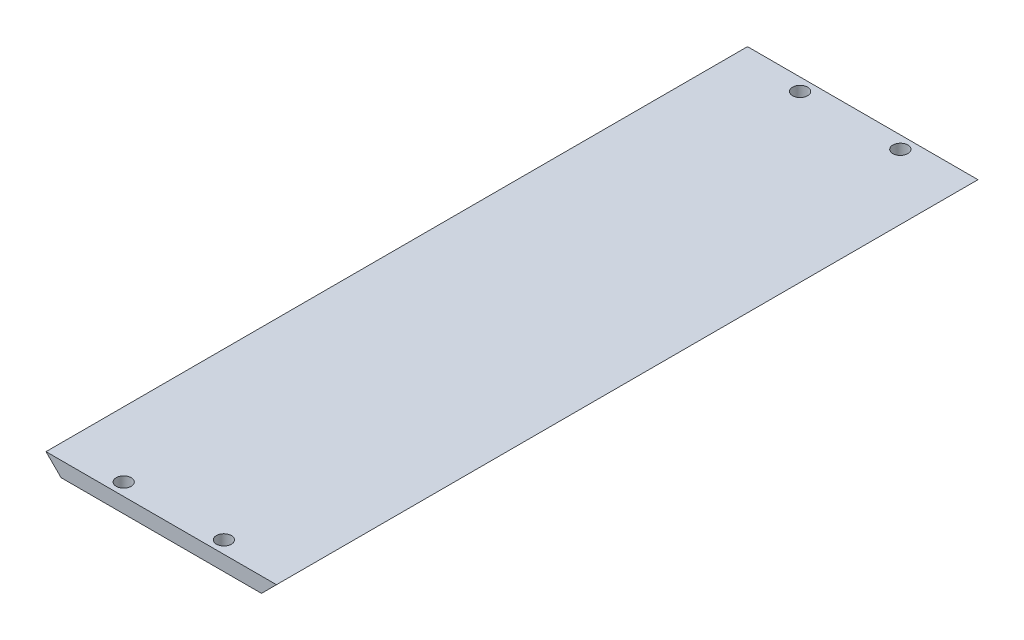
SolidWorks part; units mm, degrees
material "PET"
ref_plane "Front Plane" through (0, 0, 0) normal (0, 0, 1) x (1, 0, 0)
ref_plane "Top Plane" through (0, 0, 0) normal (0, 1, 0) x (1, 0, 0)
ref_plane "Right Plane" through (0, 0, 0) normal (1, 0, 0) x (0, 0, -1)
sketch "Sketch1" plane through (0, 0, 0) normal (0, 1, 0) x (1, 0, 0)
  line L1 (-25, -70) -> (25, -70)
  line L2 (-25, -70) -> (-25, 70)
  line L3 (-25, 70) -> (25, 70)
  line L4 (25, -70) -> (25, 70)
  line L5 (-25, -70) -> (25, 70) construction
  line L6 (-25, 70) -> (25, -70) construction
  point P0 (0, 0)
  dimension "D1" = 50
  dimension "D2" = 140
extrude "Boss-Extrude2" add sketch "Sketch1" along normal blind 5
sketch "Sketch2" plane through (0, 0, 70) normal (0, 0, 1) x (1, 0, 0)
  line L0 (-25, 0) -> (25, 0) construction
  line L5 (-25, 5) -> (-20, 0)
  line L7 (25, 5) -> (20, 0)
  line M2 (-25, 0) -> (25, 0)
  line M3 (25, 0) -> (25, 5)
  line M5 (-25, 5) -> (-25, 0)
extrude "Cut-Extrude1" cut sketch "Sketch2" against normal blind 152 contours L5 M5 M2 | L7 M3 M2
sketch "Sketch7" plane through (0, 0, -70) normal (0, 0, -1) x (-1, 0, 0)
  line L1 (-25, 5) -> (25, 5)
  line L2 (-25, 5) -> (-25, 3)
  line L3 (-25, 3) -> (25, 3)
  line L4 (25, 5) -> (25, 3)
  dimension "D1" = 2
extrude "Cut-Extrude5" cut sketch "Sketch7" against normal blind 197
sketch "Sketch8" plane through (0, 0, 0) normal (0, -1, 0) x (1, 0, 0)
  line L1 (-15, -65) -> (15, -65)
  line L2 (-15, -65) -> (-15, 65)
  line L3 (-15, 65) -> (15, 65)
  line L4 (15, -65) -> (15, 65)
  line L5 (-15, -65) -> (15, 65) construction
  line L6 (-15, 65) -> (15, -65) construction
  point P0 (0, 0)
  dimension "D1" = 30
  dimension "D2" = 130
extrude "Cut-Extrude6" cut sketch "Sketch8" against normal blind 197
sketch "Sketch9" plane through (0, 0, 0) normal (0, -1, 0) x (1, 0, 0)
  line L0 (20, 70) -> (20, -70) construction
  line L1 (-20, -70) -> (20, -70)
  line L2 (-20, -70) -> (-20, -50)
  line L3 (-20, -50) -> (20, -50)
  line L4 (20, -70) -> (20, -50)
  circle A0 centre (-13.5, -56.5) radius 1.5
  circle A1 centre (13.5, -56.5) radius 1.5
  dimension "D1" = 20
extrude "Boss-Extrude5" add sketch "Sketch9" against normal blind 3
sketch "Sketch10" plane through (0, 0, 0) normal (0, -1, 0) x (1, 0, 0)
  line L0 (15, -50) -> (15, 65) construction
  line L5 (-20, 70) -> (-20, -70) construction
  line L6 (-15, 55) -> (15, 55)
  line L7 (-15, 55) -> (-15, 45)
  line L8 (-15, 45) -> (15, 45)
  line L9 (15, 55) -> (15, 45)
  line L10 (-20, 55) -> (20, 55)
  line L11 (-20, 55) -> (-20, 45)
  line L12 (-20, 45) -> (20, 45)
  line L13 (20, 55) -> (20, 45)
  line L14 (20, 70) -> (20, -70) construction
  circle A0 centre (-10, 50) radius 1.5
  circle A1 centre (10, 50) radius 1.5
  line M16 (15, 65) -> (15, -50)
  line M18 (-15, -50) -> (-15, 65)
extrude "Boss-Extrude6" add sketch "Sketch10" against normal blind 3 contours L8 L6 A0 A1 M18 M16
sketch "Sketch11" plane through (0, 0, 0) normal (0, -1, 0) x (1, 0, 0)
  line L0 (-20, 0) -> (0, 0)
  line L4 (-20, 70) -> (-20, -70) construction
  circle A0 centre (-10, 67.5) radius 1.5
  circle A1 centre (10, 67.5) radius 1.5
  circle A2 centre (10, -67.5) radius 1.5
  circle A3 centre (-10, -67.5) radius 1.5
extrude "Cut-Extrude7" cut sketch "Sketch11" against normal blind 3 contours A3 | A2 | A1 | A0
sketch "Sketch12" plane through (0, 3, 0) normal (0, 1, 0) x (1, 0, 0)
  line L1 (15, -65) -> (-15.0401, -65)
  line L2 (15, -65) -> (15, 61.5204)
  line L3 (15, 61.5204) -> (-15.0401, 61.5204)
  line L4 (-15.0401, -65) -> (-15.0401, 61.5204)
extrude "Boss-Extrude8" add sketch "Sketch12" against normal blind 3
